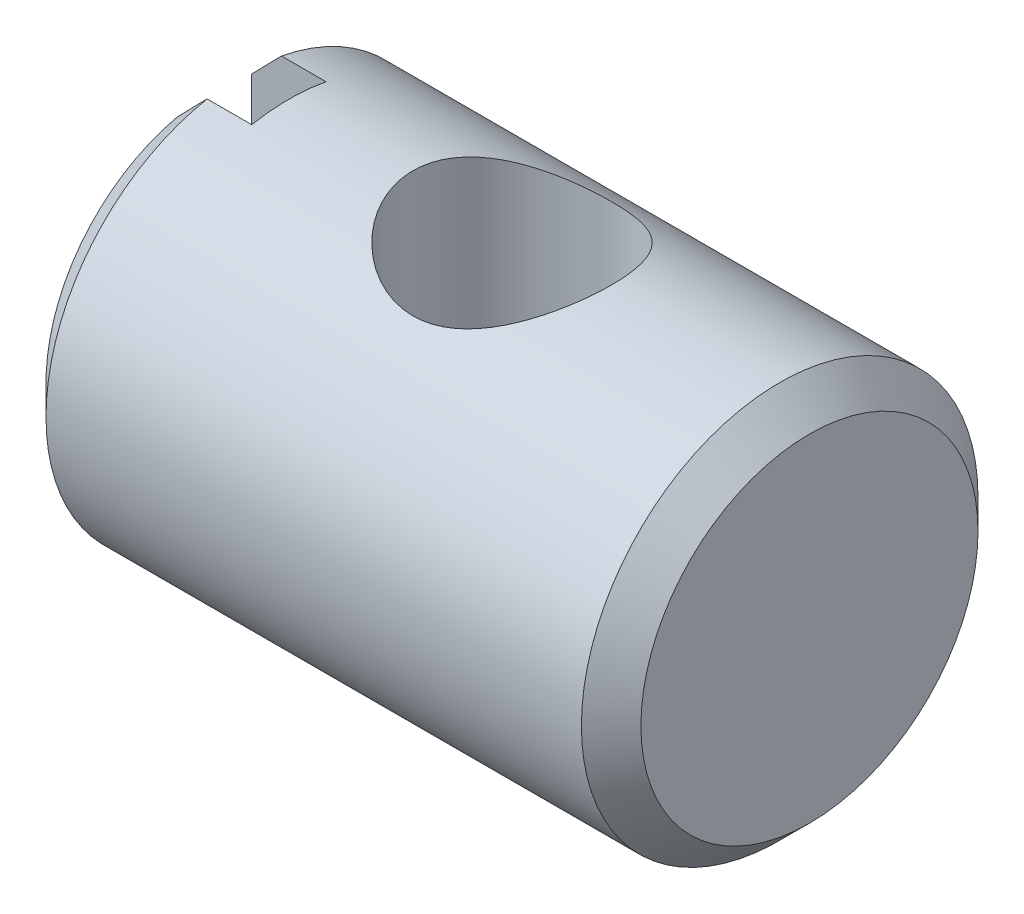
SolidWorks part; units mm, degrees
material "Plain Carbon Steel"
ref_plane "Front Plane" through (0, 0, 0) normal (0, 0, 1) x (1, 0, 0)
ref_plane "Top Plane" through (0, 0, 0) normal (0, 1, 0) x (1, 0, 0)
ref_plane "Right Plane" through (0, 0, 0) normal (1, 0, 0) x (0, 0, -1)
sketch "Sketch1" plane through (0, 0, 0) normal (1, 0, 0) x (0, 0, -1)
  circle A0 centre (0, 0) radius 4
  dimension "D1" = 8
extrude "Boss-Extrude1" add sketch "Sketch1" along normal mid plane 12
chamfer "Chamfer1" distance 0.6 angle 45 2 edges at (-6, 0, -4) (6, 0, -4)
sketch "Sketch2" plane through (0, 0, 0) normal (0, 1, 0) x (1, 0, 0)
  circle A0 centre (0, 0) radius 2
  dimension "D1" = 4
extrude "Cut-Extrude1" cut sketch "Sketch2" against normal through all both and the other way through all
sketch "Sketch3" plane through (-6, 0, 0) normal (-1, 0, 0) x (0, 0, 1)
  line L0 (-0.75, -5.0894) -> (-0.75, 5.0894)
  line L1 (-0.75, -5.0894) -> (0.75, -5.0894)
  line L2 (-0.75, 5.0894) -> (0.75, 5.0894)
  line L3 (0.75, -5.0894) -> (0.75, 5.0894)
  line L4 (-0.75, -5.0894) -> (0.75, 5.0894) construction
  line L5 (-0.75, 5.0894) -> (0.75, -5.0894) construction
  point P1 (0, 0)
  dimension "D1" = 1.5
extrude "Cut-Extrude2" cut sketch "Sketch3" against normal blind 1.5
